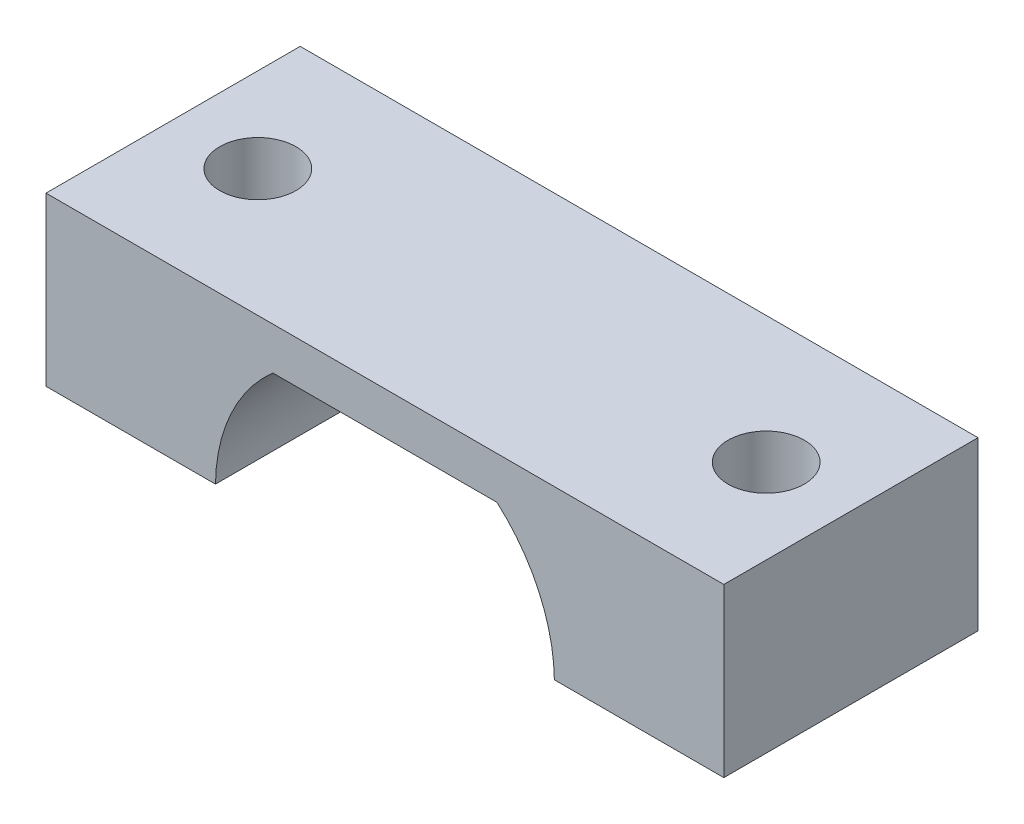
SolidWorks part; units mm, degrees
material "ABS"
ref_plane "Front Plane" through (0, 0, 0) normal (0, 0, 1) x (1, 0, 0)
ref_plane "Top Plane" through (0, 0, 0) normal (0, 1, 0) x (1, 0, 0)
ref_plane "Right Plane" through (0, 0, 0) normal (1, 0, 0) x (0, 0, -1)
sketch "Motor Clamp Outline Sketch" plane through (0, 0, 0) normal (0, 0, 1) x (1, 0, 0)
  line L0 (-20, 0.125) -> (-9.9992, 0.125)
  line L1 (-20, 10) -> (20, 10) construction
  line L2 (-20, 10) -> (-20, 0) construction
  line L3 (-20, 0) -> (20, 0) construction
  line L4 (20, 10) -> (20, 0) construction
  line L5 (-20, 10) -> (20, 0) construction
  line L6 (-20, 0) -> (20, 10) construction
  line L7 (-20, 0.125) -> (-20, 10)
  line L8 (-20, 10) -> (20, 10)
  line L9 (20, 10) -> (20, 0.125)
  line L10 (9.9992, 0.125) -> (20, 0.125)
  line L11 (-6.6144, 7.5) -> (6.6144, 7.5)
  line L12 (-20, 0.125) -> (20, 0.125) construction
  arc A0 (9.9992, 0.125) -> (-9.9992, 0.125) centre (0, 0) ccw construction
  arc A1 (9.9992, 0.125) -> (6.6144, 7.5) centre (0, 0) ccw
  arc A2 (-6.6144, 7.5) -> (-9.9992, 0.125) centre (0, 0) ccw
  point P3 (0, 5)
  dimension "D2" = 20
  dimension "D1" = 40
  dimension "D3" = 10
  dimension "D5" = 2.5
  dimension "D4" = 0.125
extrude "Motor Clamp Outline Solid" add sketch "Motor Clamp Outline Sketch" along normal mid plane 15
sketch "Motor Clamp Mounting Holes Sketch" plane through (0, 10, 0) normal (0, 1, 0) x (1, 0, 0)
  line L0 (-15, 0) -> (15, 0) construction
  circle A0 centre (-15, 0) radius 2.25
  circle A1 centre (15, 0) radius 2.25
  point P4 (0, 0)
  dimension "D1" = 4.5
  dimension "D2" = 30
extrude "Motor Clamp Mounting Hole Cut" cut sketch "Motor Clamp Mounting Holes Sketch" against normal through all
